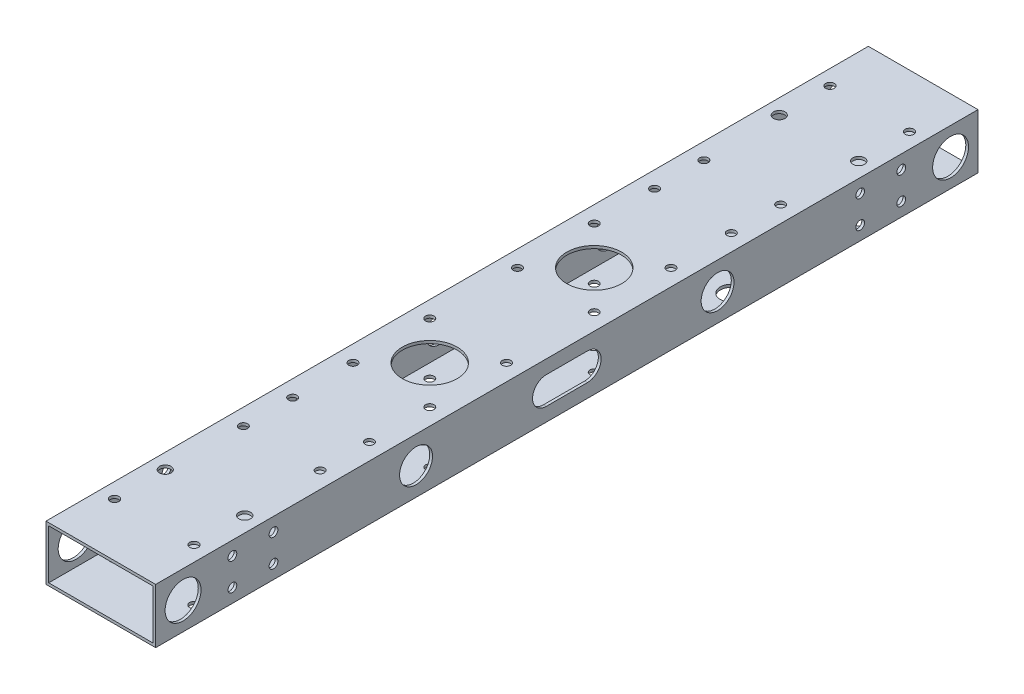
SolidWorks part; units mm, degrees
material "6061 合金"
ref_plane "前视基准面" through (0, 0, 0) normal (0, 0, 1) x (1, 0, 0)
ref_plane "上视基准面" through (0, 0, 0) normal (0, 1, 0) x (1, 0, 0)
ref_plane "右视基准面" through (0, 0, 0) normal (1, 0, 0) x (0, 0, -1)
other "Configuration Table"
sketch "草图1" plane through (0, 0, 0) normal (0, 0, 1) x (1, 0, 0)
  line L1 (-20, 10) -> (20, 10)
  line L2 (-20, 10) -> (-20, -10)
  line L3 (-20, -10) -> (20, -10)
  line L4 (20, 10) -> (20, -10)
  line L5 (-20, 10) -> (20, -10) construction
  line L6 (-20, -10) -> (20, 10) construction
  line L7 (-19, 9) -> (19, 9)
  line L8 (-19, 9) -> (-19, -9)
  line L9 (-19, -9) -> (19, -9)
  line L10 (19, 9) -> (19, -9)
  line L11 (-19, 9) -> (19, -9) construction
  line L12 (-19, -9) -> (19, 9) construction
  point P0 (0, 0)
  point P6 (0, 0)
  dimension "D1" = 1
  dimension "D2" = 20
  dimension "D3" = 40
  dimension "D4" = 1
extrude "凸台-拉伸1" add sketch "草图1" along normal mid plane 300
sketch "草图2" plane through (20, 0, 0) normal (1, 0, 0) x (0, 0, -1)
  line L0 (140, 0) -> (-140, 0) construction
  circle A0 centre (-140, 0) radius 6.55
  circle A1 centre (140, 0) radius 6.55
  dimension "D2" = 13.1
  dimension "D1" = 280
extrude "切除-拉伸1" cut sketch "草图2" against normal blind 40
sketch "草图3" plane through (0, 10, 0) normal (0, 1, 0) x (1, 0, 0)
  line L1 (-14, -66) -> (14, -66) construction
  line L2 (-14, -66) -> (-14, -84) construction
  line L3 (-14, -84) -> (14, -84) construction
  line L4 (14, -66) -> (14, -84) construction
  line L5 (20, -150) -> (20, 150) construction
  line L7 (-14, 84) -> (14, 84) construction
  line L8 (-14, 84) -> (-14, 66) construction
  line L9 (-14, 66) -> (14, 66) construction
  line L10 (14, 84) -> (14, 66) construction
  circle A0 centre (-14, -84) radius 1.55
  circle A1 centre (-14, -66) radius 1.55
  circle A2 centre (14, -84) radius 1.55
  circle A3 centre (14, -66) radius 1.55
  circle A4 centre (-14, 66) radius 1.55
  circle A5 centre (-14, 84) radius 1.55
  circle A6 centre (14, 66) radius 1.55
  circle A7 centre (14, 84) radius 1.55
  dimension "D1" = 3.1
  dimension "D4" = 3.1
  dimension "D2" = 6
  dimension "D3" = 6
extrude "切除-拉伸2" cut sketch "草图3" against normal blind 30
sketch "草图4" plane through (0, -10, 0) normal (0, -1, 0) x (1, 0, 0)
  circle A0 centre (14, -84) radius 4
  circle A1 centre (14, -66) radius 4
  circle A2 centre (14, 84) radius 4
  circle A3 centre (14, 66) radius 4
  dimension "D1" = 8
extrude "切除-拉伸3" cut sketch "草图4" against normal blind 10
sketch "草图5" plane through (20, 0, 0) normal (1, 0, 0) x (0, 0, -1)
  line L0 (0, -67.4871) -> (0, 54) construction
  circle A0 centre (122, 5) radius 1.6
  circle A1 centre (122, -5) radius 1.6
  circle A2 centre (107, 5) radius 1.6
  circle A3 centre (107, -5) radius 1.6
  circle A4 centre (-107, -5) radius 1.6
  circle A5 centre (-107, 5) radius 1.6
  circle A6 centre (-122, -5) radius 1.6
  circle A7 centre (-122, 5) radius 1.6
  dimension "D1" = 3.2
extrude "切除-拉伸4" cut sketch "草图5" against normal blind 50
sketch "草图6" plane through (0, -10, 0) normal (0, -1, 0) x (1, 0, 0)
  line L0 (-30.3644, 0) -> (23.4085, 0) construction
  circle A0 centre (-14.5, -130.5) radius 1.6
  circle A1 centre (14.5, -130.5) radius 1.6
  circle A2 centre (14.5, -112) radius 2.1
  circle A3 centre (-14.5, -112) radius 2.1
  circle A4 centre (-14.5, 112) radius 2.1
  circle A5 centre (14.5, 112) radius 2.1
  circle A6 centre (14.5, 130.5) radius 1.6
  circle A7 centre (-14.5, 130.5) radius 1.6
  dimension "D1" = 4.2
  dimension "D2" = 3.2
extrude "切除-拉伸5" cut sketch "草图6" against normal blind 50
sketch "草图7" plane through (0, 10, 0) normal (0, 1, 0) x (1, 0, 0)
  line L0 (0, 0) -> (35.8521, 0) construction
  line L1 (-14, -16) -> (14, -44) construction
  line L2 (-14, 44) -> (14, 44) construction
  line L3 (-14, 44) -> (-14, 16) construction
  line L4 (-14, 16) -> (14, 16) construction
  line L5 (14, 44) -> (14, 16) construction
  line L6 (-14, 44) -> (14, 16) construction
  line L7 (-14, 16) -> (14, 44) construction
  line L8 (-14, -44) -> (14, -16) construction
  line L9 (14, -44) -> (14, -16) construction
  line L10 (-14, -16) -> (14, -16) construction
  line L11 (-14, -44) -> (-14, -16) construction
  line L12 (-14, -44) -> (14, -44) construction
  circle A0 centre (0, 30) radius 10
  circle A2 centre (14, 44) radius 1.55
  circle A3 centre (-14, 44) radius 1.55
  circle A4 centre (-14, 16) radius 1.55
  circle A5 centre (14, 16) radius 1.55
  circle A6 centre (14, -16) radius 1.55
  circle A7 centre (-14, -16) radius 1.55
  circle A8 centre (-14, -44) radius 1.55
  circle A9 centre (14, -44) radius 1.55
  circle A10 centre (0, -30) radius 10
  dimension "D2" = 20
  dimension "D4" = 3.1
  dimension "D1" = 30
  dimension "D3" = 28
extrude "切除-拉伸6" cut sketch "草图7" against normal blind 30
sketch "草图10" plane through (20, 0, 0) normal (1, 0, 0) x (0, 0, -1)
  line L0 (-7.5, 0) -> (7.5, 0) construction
  line L1 (-7.5, 5) -> (7.5, 5)
  line L2 (-7.5, -5) -> (7.5, -5)
  line L3 (0, -36.9219) -> (0, 24.72) construction
  arc A0 (-7.5, 5) -> (-7.5, -5) centre (-7.5, 0) ccw
  arc A1 (7.5, -5) -> (7.5, 5) centre (7.5, 0) ccw
  circle A2 centre (55, 0) radius 6
  circle A3 centre (-55, 0) radius 6
  point P2 (0, 0)
  dimension "D2" = 5
  dimension "D4" = 12
  dimension "D1" = 15
  dimension "D3" = 55
extrude "切除-拉伸7" cut sketch "草图10" against normal blind 50
